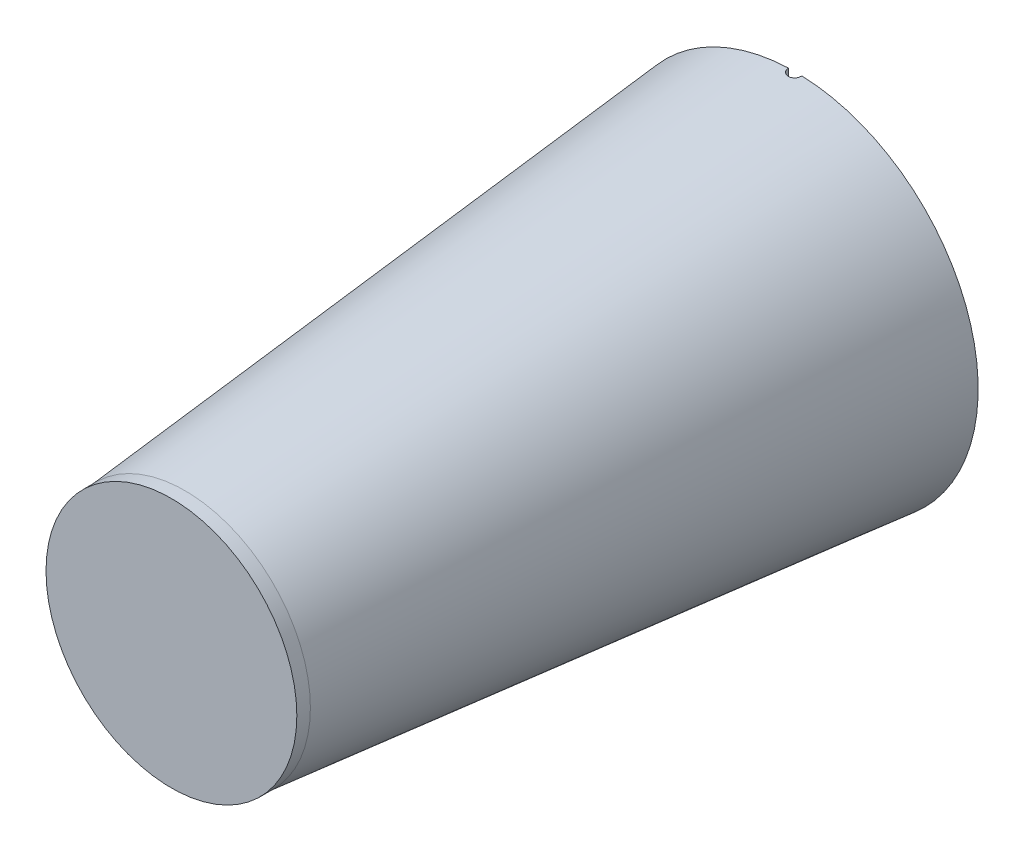
SolidWorks part; units mm, degrees
ref_plane "Front Plane" through (0, 0, 0) normal (0, 0, 1) x (1, 0, 0)
ref_plane "Top Plane" through (0, 0, 0) normal (0, 1, 0) x (1, 0, 0)
ref_plane "Right Plane" through (0, 0, 0) normal (1, 0, 0) x (0, 0, -1)
sketch "Sketch2" plane through (0, 0, 0) normal (0, 1, 0) x (1, 0, 0)
  line L0 (0, 0) -> (0, 142.875) construction
  line L1 (29.3687, 0) -> (0, 0)
  line L2 (0, 142.875) -> (42.8625, 142.875)
  line L3 (42.8625, 142.875) -> (29.3687, 0)
  line L4 (0, 142.875) -> (0, 0)
  dimension "D1" = 29.3687
  dimension "D2" = 42.8625
  dimension "D3" = 142.875
revolve "Revolve1" add sketch "Sketch2" angle 360 about L0
shell "Shell3" thickness 3.175
ref_point "Point1"
sketch "Sketch5" plane through (0, 0, 0) normal (0, 0, 1) x (1, 0, 0)
  circle A0 centre (0, 0) radius 29.3688
  circle A1 centre (0, 0) radius 29.3687 construction
extrude "Boss-Extrude1" add sketch "Sketch5" along normal blind 3.175
fillet "Fillet1" radius 3.175 1 edges at (26.4795, 0, -3.175)
ref_point "Point2"
sketch "Sketch6" plane through (0, 0, 0) normal (0, 1, 0) x (1, 0, 0)
  line L0 (0, 142.875) -> (0, 0) construction
  line L1 (42.8625, 142.875) -> (-42.8625, 142.875) construction
  line L2 (29.3687, 0) -> (-29.3687, 0) construction
  circle A0 centre (0, 142.875) radius 1.5875
  dimension "D1" = 3.175
extrude "Cut-Extrude1" cut sketch "Sketch6" against normal through all and the other way through all
ref_plane "Plane1" through (0, -29.1091, 2.7492) normal (0, -0.9956, 0.094) x (1, 0, 0)
ref_plane "Plane2" through (0, 29.1091, 2.7492) normal (0, 0.9956, 0.094) x (-1, 0, 0)
ref_plane "Plane3" through (0, 42.7126, 0) normal (0, 1, 0) x (-1, 0, 0)
